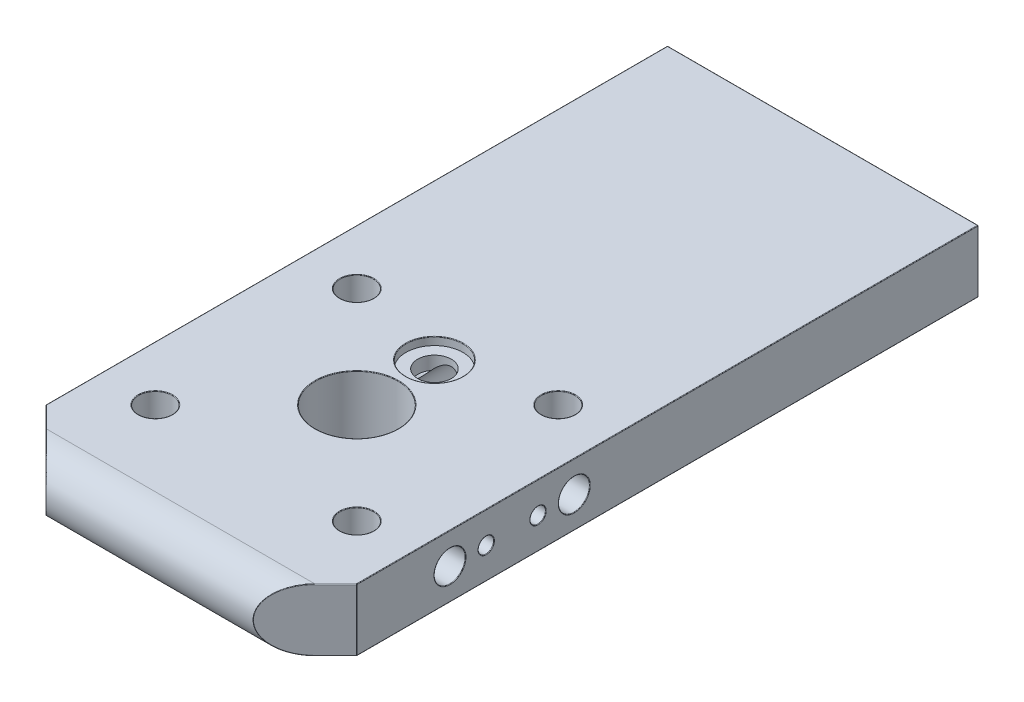
SolidWorks part; units mm, degrees
ref_plane "Front Plane" through (0, 0, 0) normal (0, 0, 1) x (1, 0, 0)
ref_plane "Top Plane" through (0, 0, 0) normal (0, 1, 0) x (1, 0, 0)
ref_plane "Right Plane" through (0, 0, 0) normal (1, 0, 0) x (0, 0, -1)
sketch "Sketch1" plane through (0, 0, 0) normal (0, 1, 0) x (1, 0, 0)
  line L0 (30, -132.6471) -> (30, -47.3529) construction
  line L1 (0, 0) -> (60, 0)
  line L2 (0, 0) -> (0, -130)
  line L3 (0, -130) -> (60, -130)
  line L4 (60, 0) -> (60, -130)
  line L6 (30, -90) -> (49.4454, -70.5546) construction
  circle A0 centre (30, -90) radius 27.5 construction
  circle A1 centre (30, -90) radius 8
  circle A2 centre (49.4454, -70.5546) radius 3.25
  circle A3 centre (49.4454, -109.4454) radius 3.25
  circle A4 centre (10.5546, -109.4454) radius 3.25
  circle A5 centre (10.5546, -70.5546) radius 3.25
  point P4 (30, -130)
  point P14 (30, -90)
  dimension "D3" = 55
  dimension "D5" = 16
  dimension "D6" = 6.5
  dimension "D1" = 130
  dimension "D2" = 60
  dimension "D4" = 90
  dimension "D7" = 4
extrude "Boss-Extrude1" add sketch "Sketch1" against normal blind 12
chamfer "Chamfer1" distance 10 angle 45 2 edges at (60, -6, 130) (0, -6, 130)
ref_plane "Plane1" through (30, 0, 0) normal (-1, 0, 0) x (0, 0, 1)
sketch "Sketch2" plane through (30, 0, 0) normal (-1, 0, 0) x (0, 0, 1)
  line L1 (120, 0) -> (130, 0) construction
  line L2 (130, -12) -> (120, -12) construction
  line L3 (130, 0) -> (130, -12) construction
  line L4 (124, 0) -> (124, -12)
  line L5 (130, -12) -> (124, -12)
  line L6 (130, 0) -> (130, -12)
  line L7 (124, 0) -> (130, 0)
  arc A0 (124, 0) -> (124, -12) centre (124, -6) cw
  dimension "D1" = 6
extrude "Cut-Extrude1" cut sketch "Sketch2" against normal through all both and the other way through all contours L7 A0 L6 | L6 A0 L5
hole_wizard "M6x1.0 Tapped Hole1" positions "Sketch3" profile "Sketch5" tap size "M6x1.0" standard "ANSI Metric"
sketch "Sketch3" plane through (0, 0, 0) normal (0, 0, -1) x (-1, 0, 0)
  line L0 (-60, 0) -> (0, 0) construction
  point P0 (-50, -6)
  point P12 (-30, 0)
  dimension "D1" = 6
  dimension "D2" = 20
sketch "Sketch5" plane through (50, -6, 0) normal (1, 0, 0) x (0, 1, 0)
  line L0 (0, 0) -> (0, 20)
  line L1 (0, 20) -> (2.5, 18.4978)
  line L2 (2.5, 18.4978) -> (2.5, 15)
  line L3 (2.5, 15) -> (3, 15)
  line L4 (3, 15) -> (3, 0)
  line L5 (3, 0) -> (0, 0)
  line L10 (0, 20) -> (-2.5, 18.4978) construction
  line L11 (0, -6.35) -> (0, 107.95) construction
  dimension "Tap Drill Dia." = 5
  dimension "Tap Drill Depth" = 20
  dimension "Thread Major Dia." = 6
  dimension "Thread Depth" = 15
  dimension "Drill Angle" = 118
hole_wizard "Ø5.0mm Dowel Hole1" positions "Sketch6" profile "Sketch8" hole size "Ø5.0" standard "ANSI Metric"
sketch "Sketch6" plane through (0, 0, 0) normal (0, 0, -1) x (-1, 0, 0)
  point P0 (-40, -6)
  dimension "D1" = 10
sketch "Sketch8" plane through (40, -6, 0) normal (1, 0, 0) x (0, 1, 0)
  line L0 (0, 0) -> (0, 16.5022)
  line L1 (0, 16.5022) -> (2.5, 15)
  line L2 (2.5, 15) -> (2.5, 0)
  line L5 (2.5, 0) -> (0, 0)
  line L10 (0, 16.5022) -> (-2.5, 15) construction
  line L11 (0, -6.35) -> (0, 107.95) construction
  dimension "Hole Dia." = 5
  dimension "Hole Depth" = 15
  dimension "Drill Angle" = 118
mirror "Mirror1" about plane through (30, 0, 0) normal (-1, 0, 0) of "Ø5.0mm Dowel Hole1", "M6x1.0 Tapped Hole1"
hole_wizard "Ø6.0mm Dowel Hole1" positions "Sketch10" profile "Sketch11" hole size "Ø6.0" standard "ANSI Metric"
sketch "Sketch10" plane through (0, 0, 0) normal (0, 0, -1) x (-1, 0, 0)
  point P0 (-30, -6)
  dimension "D1" = 10
sketch "Sketch11" plane through (30, -6, 0) normal (1, 0, 0) x (0, 1, 0)
  line L0 (0, 0) -> (0, 80.4528)
  line L1 (0, 80.4528) -> (3.25, 78.5)
  line L2 (3.25, 78.5) -> (3.25, 0)
  line L5 (3.25, 0) -> (0, 0)
  line L10 (0, 80.4528) -> (-3.25, 78.5) construction
  line L11 (0, -6.35) -> (0, 107.95) construction
  dimension "Hole Dia." = 6.5
  dimension "Hole Depth" = 78.5
  dimension "Drill Angle" = 118
hole_wizard "Ø3.0mm Dowel Hole1" positions "Sketch12" profile "Sketch13" hole size "Ø3.0" standard "ANSI Metric"
sketch "Sketch12" plane through (60, 0, 0) normal (1, 0, 0) x (0, 0, -1)
  line L0 (-120, 0) -> (0, 0) construction
  point P0 (-85, -6)
  dimension "D1" = 85
  dimension "D2" = 6
sketch "Sketch13" plane through (60, -6, 85) normal (0, 1, 0) x (0, 0, -1)
  line L0 (0, 0) -> (0, 12)
  line L1 (0, 12) -> (1.5, 11.0987)
  line L2 (1.5, 11.0987) -> (1.5, 0)
  line L5 (1.5, 0) -> (0, 0)
  line L10 (0, 12) -> (-1.5, 11.0987) construction
  line L11 (0, -6.35) -> (0, 107.95) construction
  dimension "Hole Dia." = 3
  dimension "Hole Depth" = 12
  dimension "Drill Angle" = 118
hole_wizard "M6x1.0 Tapped Hole2" positions "Sketch14" profile "Sketch15" tap size "M6x1.0" standard "ANSI Metric"
sketch "Sketch14" plane through (60, 0, 0) normal (1, 0, 0) x (0, 0, -1)
  line L0 (0, -12) -> (0, 0) construction
  point P0 (-78, -6)
  dimension "D1" = 78
sketch "Sketch15" plane through (60, -6, 78) normal (0, 1, 0) x (0, 0, -1)
  line L0 (0, 0) -> (0, 20)
  line L1 (0, 20) -> (2.5, 18.4978)
  line L2 (2.5, 18.4978) -> (2.5, 15)
  line L3 (2.5, 15) -> (3, 15)
  line L4 (3, 15) -> (3, 0)
  line L5 (3, 0) -> (0, 0)
  line L10 (0, 20) -> (-2.5, 18.4978) construction
  line L11 (0, -6.35) -> (0, 107.95) construction
  dimension "Tap Drill Dia." = 5
  dimension "Tap Drill Depth" = 20
  dimension "Thread Major Dia." = 6
  dimension "Thread Depth" = 15
  dimension "Drill Angle" = 118
ref_plane "Plane2" through (0, 0, 90) normal (0, 0, 1) x (1, 0, 0)
mirror "Mirror2" about plane through (0, 0, 90) normal (0, 0, 1) of "Ø3.0mm Dowel Hole1", "M6x1.0 Tapped Hole2"
hole_wizard "CBORE for M6 Hex Head Bolt1" positions "Sketch16" profile "Sketch18" counterbore size "M6" standard "ANSI Metric"
sketch "Sketch16" plane through (0, 0, 0) normal (0, 1, 0) x (1, 0, 0)
  line L0 (0, 0) -> (0, -120) construction
  line L1 (60, 0) -> (0, 0) construction
  point P0 (30, -75)
  dimension "D1" = 30
  dimension "D2" = 75
sketch "Sketch18" plane through (30, 0, 75) normal (1, 0, 0) x (0, 0, 1)
  line L0 (0, 0) -> (0, 6)
  line L1 (0, 6) -> (3.25, 4.0472)
  line L2 (3.25, 4.0472) -> (3.25, 1.5)
  line L3 (3.25, 1.5) -> (5.5, 1.5)
  line L4 (5.5, 1.5) -> (5.5, 0)
  line L5 (5.5, 0) -> (0, 0)
  line L10 (0, 6) -> (-3.25, 4.0472) construction
  line L11 (0, -6.35) -> (0, 107.95) construction
  dimension "Hole Dia." = 6.5
  dimension "Hole Depth" = 6
  dimension "C'Bore Dia." = 11
  dimension "C'Bore Depth" = 1.5
  dimension "Drill Angle" = 118
fillet "Fillet4" radius 0.1 36 edges at (10, -6, 130) (50, -6, 130) (30, 0, 80.5) (60, -6, 99) (60, -6, 93.5) (60, -6, 83.5) (26.75, -6, 0) (17.5, -6, 0) (7, -6, 0) (37.5, -6, 0) (47, -6, 0) (2, 0, 122) (58, 0, 122) (60, -6, 120) (2, -12, 122) (58, -12, 122) (0, -6, 120) (60, -6, 75) (10.5546, 0, 73.8046) (10.5546, 0, 112.6954) (10.5546, -12, 112.6954) (49.4454, 0, 112.6954) (49.4454, -12, 112.6954) (49.4454, 0, 73.8046) (30, 0, 98) (30, -12, 98) (0, 0, 60) (60, 0, 60) (30, 0, 0) (0, -12, 60) (60, -12, 60) (30, -12, 0) (60, -6, 0) (0, -6, 0) (10.5546, -12, 73.8046) (49.4454, -12, 73.8046)
